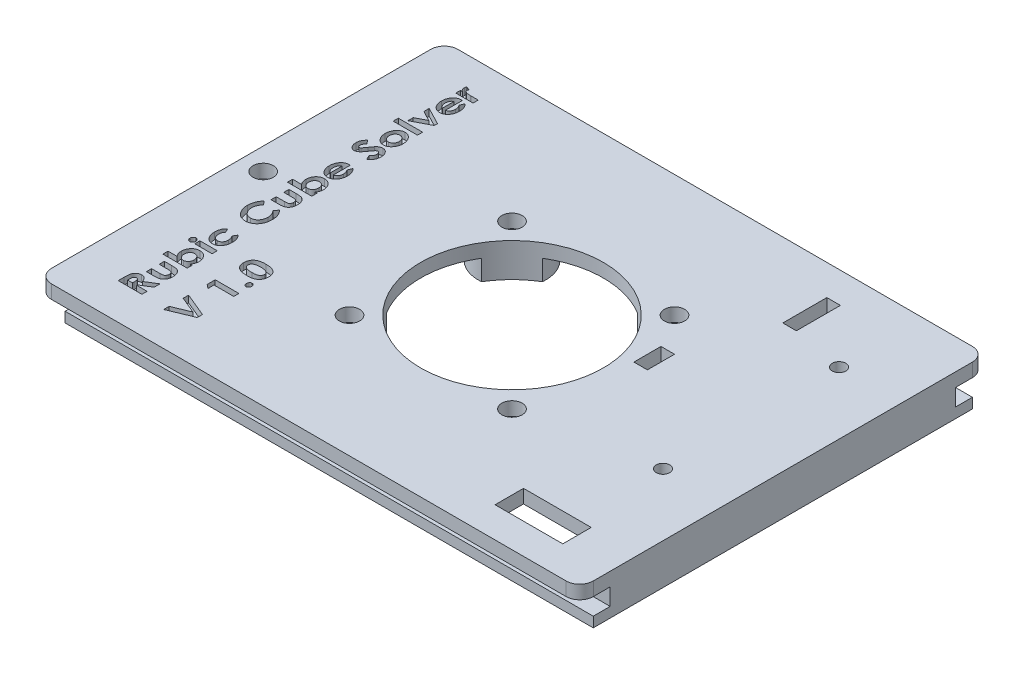
SolidWorks part; units mm, degrees
ref_plane "Front Plane" through (0, 0, 0) normal (0, 0, 1) x (1, 0, 0)
ref_plane "Top Plane" through (0, 0, 0) normal (0, 1, 0) x (1, 0, 0)
ref_plane "Right Plane" through (0, 0, 0) normal (1, 0, 0) x (0, 0, -1)
sketch "Sketch1" plane through (0, 0, 0) normal (0, 1, 0) x (1, 0, 0)
  line L1 (-40, 30) -> (40, 30)
  line L2 (-40, 30) -> (-40, -30)
  line L3 (-40, -30) -> (40, -30)
  line L4 (40, 30) -> (40, -30)
  line L5 (0, -30) -> (0, 30) construction
  line L6 (-40, 0) -> (40, 0) construction
  point P0 (0, 0)
  dimension "D1" = 60
  dimension "D2" = 80
extrude "Boss-Extrude1" add sketch "Sketch1" along normal blind 2
sketch "Sketch2" plane through (40, 0, 0) normal (1, 0, 0) x (0, 0, -1)
  line L0 (-25.5, 0) -> (-25.5, -2.5)
  line L1 (-30, 0) -> (30, 0) construction
  line L2 (-25.5, -2.5) -> (-28, -2.5)
  line L3 (-28, -2.5) -> (-28, -4)
  line L4 (-28, -4) -> (-24, -4)
  line L5 (-24, -4) -> (-24, 0)
  line L6 (-25.5, 0) -> (-24, 0)
  line L7 (0, 1.1) -> (0, -1.1) construction
  line L8 (25.5, 0) -> (24, 0)
  line L9 (24, -4) -> (24, 0)
  line L10 (28, -4) -> (24, -4)
  line L11 (28, -2.5) -> (28, -4)
  line L12 (25.5, -2.5) -> (28, -2.5)
  line L13 (25.5, 0) -> (25.5, -2.5)
  dimension "D1" = 4
  dimension "D2" = 2.5
  dimension "D3" = 4
  dimension "D4" = 2.5
  dimension "D5" = 2
extrude "Boss-Extrude2" add sketch "Sketch2" against normal blind 78
sketch "Sketch3" plane through (0, 2, 0) normal (0, 1, 0) x (1, 0, 0)
  line L0 (-1.1, 0) -> (1.1, 0) construction
  line L1 (-12, 12) -> (12, 12) construction
  line L2 (-12, 12) -> (-12, -12) construction
  line L3 (-12, -12) -> (12, -12) construction
  line L4 (12, 12) -> (12, -12) construction
  line L5 (0, -12) -> (0, 12) construction
  line L6 (-12, 0) -> (12, 0) construction
  circle A0 centre (-12, 12) radius 1.5
  circle A1 centre (-12, -12) radius 1.5
  circle A2 centre (12, -12) radius 1.5
  circle A3 centre (12, 12) radius 1.5
  point P0 (0, 0)
  dimension "D2" = 3
  dimension "D1" = 24
extrude "Cut-Extrude1" cut sketch "Sketch3" against normal up to surface (2 mm away) up to face at (0.6667, 0, 0)
sketch "Sketch4" plane through (0, 0, 0) normal (0, -1, 0) x (1, 0, 0)
  line L0 (0, -1.1) -> (0, 1.1) construction
  line L1 (-10.2679, 9) -> (-8.5359, 12)
  line L2 (-8.5359, 12) -> (-10.2679, 15)
  line L3 (-10.2679, 15) -> (-13.7321, 15)
  line L4 (-13.7321, 15) -> (-15.4641, 12)
  line L5 (-15.4641, 12) -> (-13.7321, 9)
  line L6 (-13.7321, 9) -> (-10.2679, 9)
  line L7 (13.7321, 9) -> (10.2679, 9)
  line L8 (15.4641, 12) -> (13.7321, 9)
  line L9 (13.7321, 15) -> (15.4641, 12)
  line L10 (10.2679, 15) -> (13.7321, 15)
  line L11 (8.5359, 12) -> (10.2679, 15)
  line L12 (10.2679, 9) -> (8.5359, 12)
  line L13 (1.1, 0) -> (-1.1, 0) construction
  line L14 (10.2679, -9) -> (8.5359, -12)
  line L15 (8.5359, -12) -> (10.2679, -15)
  line L16 (10.2679, -15) -> (13.7321, -15)
  line L17 (13.7321, -15) -> (15.4641, -12)
  line L18 (15.4641, -12) -> (13.7321, -9)
  line L19 (13.7321, -9) -> (10.2679, -9)
  line L20 (-13.7321, -9) -> (-10.2679, -9)
  line L21 (-15.4641, -12) -> (-13.7321, -9)
  line L22 (-13.7321, -15) -> (-15.4641, -12)
  line L23 (-10.2679, -15) -> (-13.7321, -15)
  line L24 (-8.5359, -12) -> (-10.2679, -15)
  line L25 (-10.2679, -9) -> (-8.5359, -12)
  circle A0 centre (-12, 12) radius 3 construction
  circle A1 centre (12, 12) radius 3 construction
  circle A2 centre (12, -12) radius 3 construction
  circle A3 centre (-12, -12) radius 3 construction
  circle A4 centre (-12, 12) radius 5
  circle A5 centre (12, 12) radius 5
  circle A6 centre (12, -12) radius 5
  circle A7 centre (-12, -12) radius 5
  dimension "D2" = 10
  dimension "D1" = 6
extrude "Boss-Extrude3" add sketch "Sketch4" along normal blind 3
sketch "Sketch5" plane through (0, 2, 0) normal (0, 1, 0) x (1, 0, 0)
  line L0 (-1.1, 0) -> (1.1, 0) construction
  line L1 (-22, -30) -> (-30, -30) construction
  line L2 (-22, -30) -> (-22, 30) construction
  line L3 (-22, 30) -> (-30, 30) construction
  line L4 (-30, -30) -> (-30, 30) construction
  line L5 (-40, 30) -> (-40, -30) construction
  text T0 "   Rubic Cube Solver\r\n   V 1.0" font "Century Gothic" height 3.5
  point P4 (-30, 0)
  dimension "D1" = 8
  dimension "D2" = 60
  dimension "D3" = 10
extrude "Cut-Extrude2" cut sketch "Sketch5" against normal blind 1
sketch "Sketch6" plane through (0, 2, 0) normal (0, 1, 0) x (1, 0, 0)
  line L0 (-40, 30) -> (-40, -30) construction
  line L1 (-3.3, 0) -> (3.3, 0) construction
  circle A0 centre (-36.75, 0) radius 1.5
  dimension "D1" = 3
  dimension "D2" = 3.25
extrude "Cut-Extrude3" cut sketch "Sketch6" against normal through all
sketch "Sketch7" plane through (0, 2, 0) normal (0, 1, 0) x (1, 0, 0)
  line L0 (-40, -30) -> (40, -30) construction
  line L1 (15, 15) -> (-15, 15) construction
  line L2 (15, 15) -> (15, -15) construction
  line L3 (15, -15) -> (-15, -15) construction
  line L4 (-15, 15) -> (-15, -15) construction
  line L5 (0, -15) -> (0, 15) construction
  line L6 (15, 0) -> (-15, 0) construction
  line L7 (15, 3) -> (17, 3)
  line L8 (15, 3) -> (15, 7)
  line L9 (15, 7) -> (17, 7)
  line L10 (17, 3) -> (17, 7)
  point P0 (0, 0)
  dimension "D1" = 30
  dimension "D2" = 2
  dimension "D3" = 4
  dimension "D4" = 33
extrude "Cut-Extrude4" cut sketch "Sketch7" against normal through all
sketch "Sketch8" plane through (40, 0, 0) normal (1, 0, 0) x (0, 0, -1)
  line L1 (-24, -4) -> (24, -4)
  line L2 (-24, -4) -> (-24, 0)
  line L3 (-24, 0) -> (24, 0)
  line L4 (24, -4) -> (24, 0)
extrude "Boss-Extrude4" add sketch "Sketch8" against normal blind 2
fillet "Fillet1" radius 2 4 edges at (40, 1, 30) (40, 1, -30) (-40, 1, -30) (-40, 1, 30)
sketch "Sketch9" plane through (0, 2, 0) normal (0, 1, 0) x (1, 0, 0)
  line L0 (23, 25.5) -> (23, 19) construction
  line L1 (23, 25.5) -> (33, 25.5) construction
  line L2 (15, 25.5) -> (23, 25.5) construction
  line L3 (15, 19) -> (15, 25.5) construction
  line L4 (23, 19) -> (15, 19) construction
  line L5 (33, -25.5) -> (23, -25.5) construction
  line L6 (35, -27.5) -> (35, 27.5)
  line L7 (35, 27.5) -> (13, 27.5)
  line L8 (13, 27.5) -> (13, 17)
  line L9 (13, 17) -> (21, 17)
  line L10 (21, 17) -> (21, -27.5)
  line L11 (21, -27.5) -> (35, -27.5)
  line L12 (35, -27.5) -> (35, 27.5) construction
  line L13 (35, 27.5) -> (13, 27.5) construction
  line L14 (13, 27.5) -> (13, 17) construction
  line L15 (13, 17) -> (21, 17) construction
  line L16 (21, 17) -> (21, -27.5) construction
  line L17 (21, -27.5) -> (35, -27.5) construction
  line L18 (33, 25.5) -> (33, -25.5) construction
  line L19 (23, -25.5) -> (23, 19) construction
  line L20 (23, 25.5) -> (23, 19)
  line L21 (23, 25.5) -> (33, 25.5) construction
  line L22 (15, 25.5) -> (23, 25.5) construction
  line L23 (15, 19) -> (15, 25.5) construction
  line L24 (23, 19) -> (15, 19) construction
  line L25 (33, -25.5) -> (23, -25.5) construction
  line L26 (33, 25.5) -> (33, -25.5) construction
  line L27 (23, -25.5) -> (23, 19) construction
  line L28 (21, 25.5) -> (23, 25.5)
  line L29 (23, -25.5) -> (33, -25.5)
  line L30 (23, -25.5) -> (23, -21.3)
  line L31 (23, -21.3) -> (33, -21.3)
  line L32 (33, -25.5) -> (33, -21.3)
  line L33 (23, 19) -> (21, 19)
  line L34 (23, 19) -> (23, 25.5)
  line L35 (23, 25.5) -> (21, 25.5)
  line L36 (21, 19) -> (21, 25.5)
  circle A0 centre (30.8, 17.5) radius 1.5 construction
  circle A1 centre (30.8, -8.5) radius 1.5 construction
  circle A2 centre (30.8, 17.5) radius 1.5 construction
  circle A3 centre (30.8, -8.5) radius 1.5 construction
  circle A4 centre (30.8, -8.5) radius 1
  circle A5 centre (30.8, 17.5) radius 1
  circle A6 centre (0, 0) radius 13.5
  dimension "D4" = 2
  dimension "D5" = 2
  dimension "D6" = 27
  dimension "D2" = 4.2
  dimension "D3" = 2
  dimension "D1" = 0
extrude "Cut-Extrude5" cut sketch "Sketch9" against normal through all contours L29 L32 L31 L30 | A4 | A5 | L36 L33 L20 L28 | A6
sketch "Sketch10" plane through (0, 0, -25.5) normal (0, 0, -1) x (-1, 0, 0)
  line L0 (-23, 0) -> (-40, 0) construction
  line L1 (-27, 0) -> (-22, 0)
  line L2 (-27, 0) -> (-27, -4)
  line L3 (-27, -4) -> (-22, -4)
  line L4 (-22, 0) -> (-22, -4)
  line L5 (38, -4) -> (-40, -4) construction
  line L6 (-40, -4) -> (-40, -2.5) construction
  dimension "D1" = 13
  dimension "D2" = 5
extrude "Cut-Extrude6" cut sketch "Sketch10" against normal blind 10 and the other way through all
